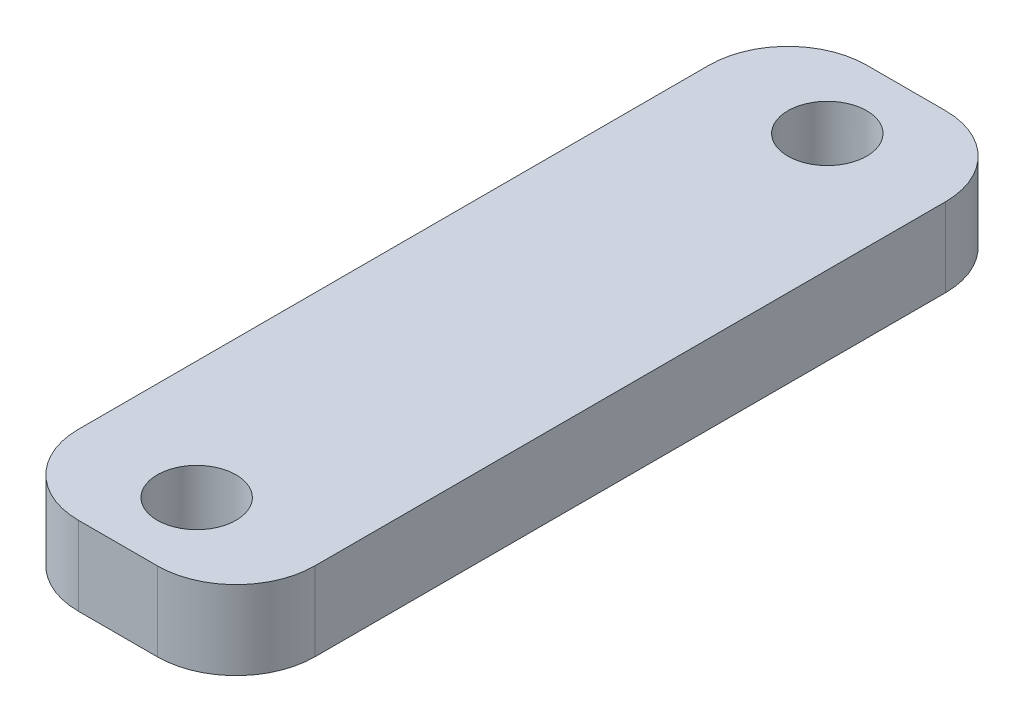
SolidWorks part; units mm, degrees
material "1060 Alloy"
ref_plane "Front Plane" through (0, 0, 0) normal (0, 0, 1) x (1, 0, 0)
ref_plane "Top Plane" through (0, 0, 0) normal (0, 1, 0) x (1, 0, 0)
ref_plane "Right Plane" through (0, 0, 0) normal (1, 0, 0) x (0, 0, -1)
sketch "Sketch1" plane through (0, 0, 0) normal (0, 1, 0) x (1, 0, 0)
  line L1 (-15, -50) -> (15, -50)
  line L2 (-15, -50) -> (-15, 50)
  line L3 (-15, 50) -> (15, 50)
  line L4 (15, -50) -> (15, 50)
  line L5 (-15, -50) -> (15, 50) construction
  line L6 (-15, 50) -> (15, -50) construction
  point P0 (0, 0)
  dimension "D1" = 30
  dimension "D2" = 100
extrude "Boss-Extrude1" add sketch "Sketch1" along normal blind 10
sketch "Sketch2" plane through (0, 10, 0) normal (0, 1, 0) x (1, 0, 0)
  line L0 (15, 50) -> (-15, 50) construction
  line L1 (0, -5.5) -> (0, 5.5) construction
  line L2 (-15, -50) -> (15, -50) construction
  circle A0 centre (0, 40) radius 5
  circle A1 centre (0, -40) radius 5
  dimension "D1" = 10
  dimension "D2" = 10
  dimension "D3" = 10
  dimension "D4" = 10
extrude "Cut-Extrude1" cut sketch "Sketch2" against normal up to surface (10 mm away) up to face at (0, 0, 0)
fillet "Fillet1" radius 10 2 edges at (-15, 5, 50) (15, 5, 50)
fillet "Fillet2" radius 10 2 edges at (15, 5, -50) (-15, 5, -50)
